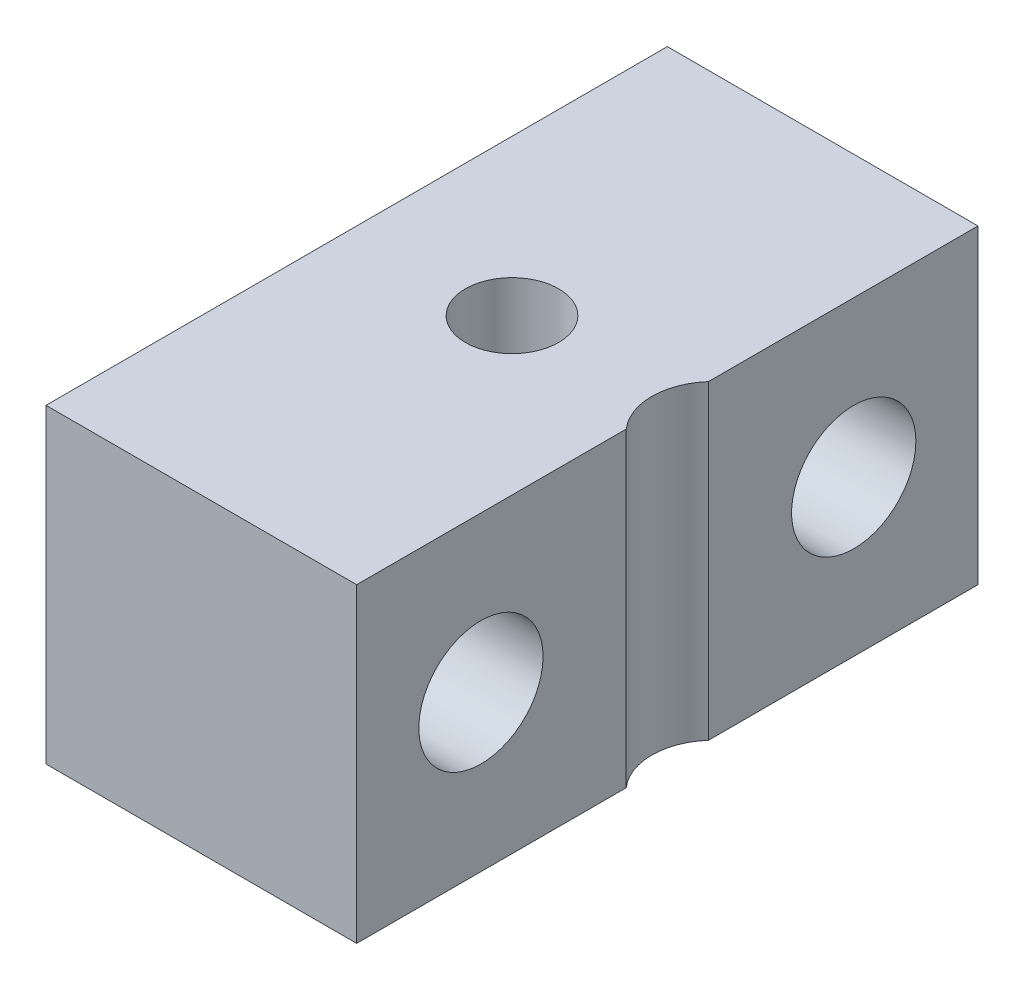
SolidWorks part; units mm, degrees
ref_plane "Front Plane" through (0, 0, 0) normal (0, 0, 1) x (1, 0, 0)
ref_plane "Top Plane" through (0, 0, 0) normal (0, 1, 0) x (1, 0, 0)
ref_plane "Right Plane" through (0, 0, 0) normal (1, 0, 0) x (0, 0, -1)
sketch "Sketch1" plane through (0, 0, 0) normal (0, 1, 0) x (1, 0, 0)
  line L0 (10, 10) -> (11.5, 10) construction
  line L1 (0, 0) -> (10, 0)
  line L2 (0, 0) -> (0, 20)
  line L3 (0, 20) -> (10, 20)
  line L4 (10, 0) -> (10, 20)
  line L5 (9.5, 10) -> (9.5, 13.5222) construction
  circle A1 centre (11.5, 10) radius 2
  dimension "D3" = 4
  dimension "D1" = 10
  dimension "D2" = 20
  dimension "D4" = 0.5
extrude "Boss-Extrude1" add sketch "Sketch1" along normal blind 10 contours A1 L4 L3 L2 L1
sketch "Sketch2" plane through (10, 0, 0) normal (1, 0, 0) x (0, 0, -1)
  line L0 (0, 10) -> (0, 0) construction
  circle A0 centre (4, 5) radius 2
  circle A1 centre (16, 5) radius 2
  point P8 (0, 5)
  dimension "D1" = 4
  dimension "D2" = 4
  dimension "D3" = 4
extrude "Cut-Extrude1" cut sketch "Sketch2" against normal blind 19
sketch "Sketch3" plane through (0, 10, 0) normal (0, 1, 0) x (1, 0, 0)
  line L0 (0, 20) -> (10, 20) construction
  line L1 (0, 0) -> (0, 20) construction
  circle A0 centre (5, 10) radius 1.5
  point P4 (5, 20)
  point P7 (0, 10)
  dimension "D1" = 3
extrude "Cut-Extrude2" cut sketch "Sketch3" against normal blind 18
